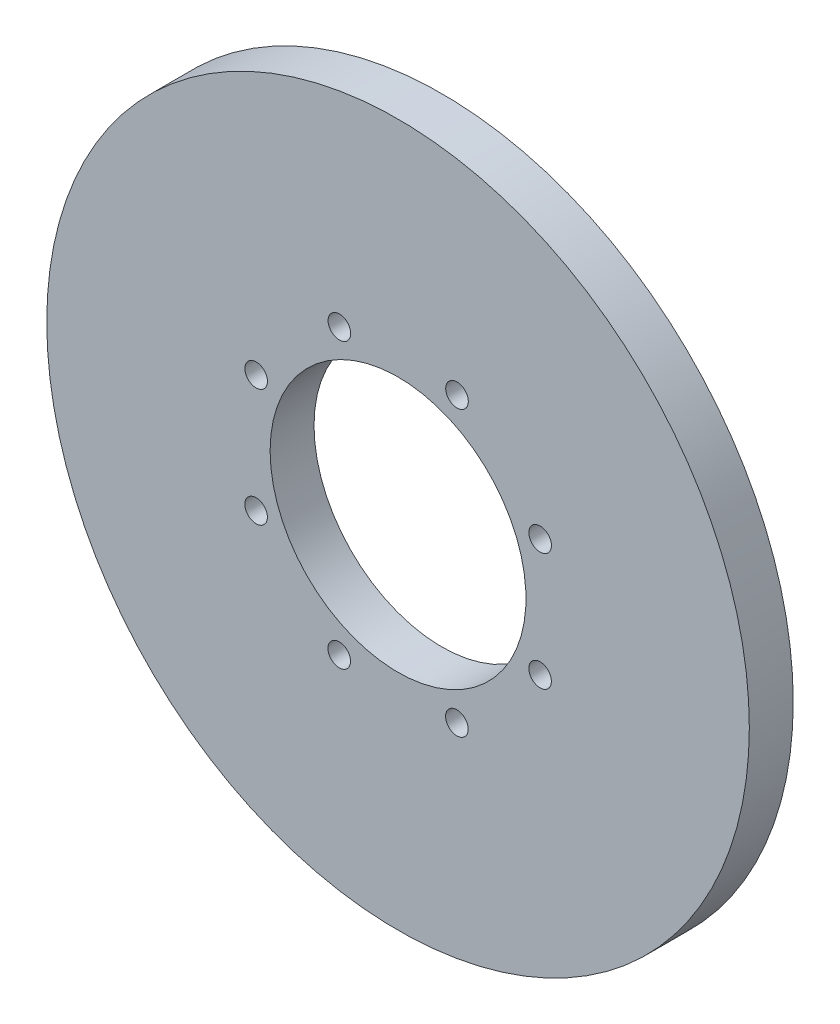
SolidWorks part; units mm, degrees
material "6061 Alloy"
ref_plane "Front Plane" through (0, 0, 0) normal (0, 0, 1) x (1, 0, 0)
ref_plane "Top Plane" through (0, 0, 0) normal (0, 1, 0) x (1, 0, 0)
ref_plane "Right Plane" through (0, 0, 0) normal (1, 0, 0) x (0, 0, -1)
sketch "Sketch1" plane through (0, 0, 0) normal (0, 0, 1) x (1, 0, 0)
  circle A0 centre (0, 0) radius 152.4
  dimension "D1" = 304.8
extrude "Boss-Extrude1" add sketch "Sketch1" along normal blind 19.05
sketch "Sketch2" plane through (0, 0, 0) normal (0, 0, -1) x (-1, 0, 0)
  circle A0 centre (0, 0) radius 65.2 construction
  dimension "D1" = 130.4
hole_wizard "3/8 (0.375) Diameter Hole1" [suppressed] positions "Sketch3" profile "Sketch4" hole size "3/8" standard "ANSI Inch"
sketch "Sketch3" plane through (0, 0, 0) normal (0, 0, -1) x (-1, 0, 0)
  circle A0 centre (0, 0) radius 65.2 construction
  point P0 (-65.2, 0)
sketch "Sketch4" plane through (65.2, 0, 0) normal (1, 0, 0) x (0, 1, 0)
  line L0 (0, 0) -> (0, 20)
  line L1 (0, 20) -> (4.7625, 20)
  line L2 (4.7625, 20) -> (4.7625, 0)
  line L5 (4.7625, 0) -> (0, 0)
  line L11 (0, -6.35) -> (0, 107.95) construction
  dimension "Thru Hole Dia." = 9.525
  dimension "Thru Hole Depth" = 20
pattern_circular "CirPattern1" [suppressed] count 8 over 360
sketch "Sketch5" plane through (0, 0, 0) normal (0, 0, -1) x (-1, 0, 0)
  circle A0 centre (0, 0) radius 55
  dimension "D1" = 110
extrude "Cut-Extrude1" cut sketch "Sketch5" against normal through all
hole_wizard "3/8 Clearance Hole1" positions "Sketch6" profile "Sketch7" hole size "3/8" standard "ANSI Inch" end condition through all
sketch "Sketch6" plane through (0, 0, 19.05) normal (0, 0, 1) x (1, 0, 0)
  point P50 (25.524, -61.673)
  point P53 (61.6247, -25.6053)
  point P56 (61.6481, 25.4255)
  point P59 (25.5804, 61.5263)
  point P62 (-25.4505, 61.5496)
  point P65 (-61.5512, 25.4819)
  point P68 (-61.5746, -25.5489)
  point P71 (-25.5069, -61.6497)
sketch "Sketch7" plane through (25.524, -61.673, 19.05) normal (1, 0, 0) x (0, -1, 0)
  line L0 (0, 0) -> (0, 19.05)
  line L1 (0, 19.05) -> (4.9022, 19.05)
  line L2 (4.9022, 19.05) -> (4.9022, 0)
  line L5 (4.9022, 0) -> (0, 0)
  line L11 (0, -6.35) -> (0, 107.95) construction
  dimension "Thru Hole Dia." = 9.8044
  dimension "Thru Hole Depth" = 19.05
other "nipple-socket-clearance" face at (-55, 0, 19.05) parameters "D1"=0.5
